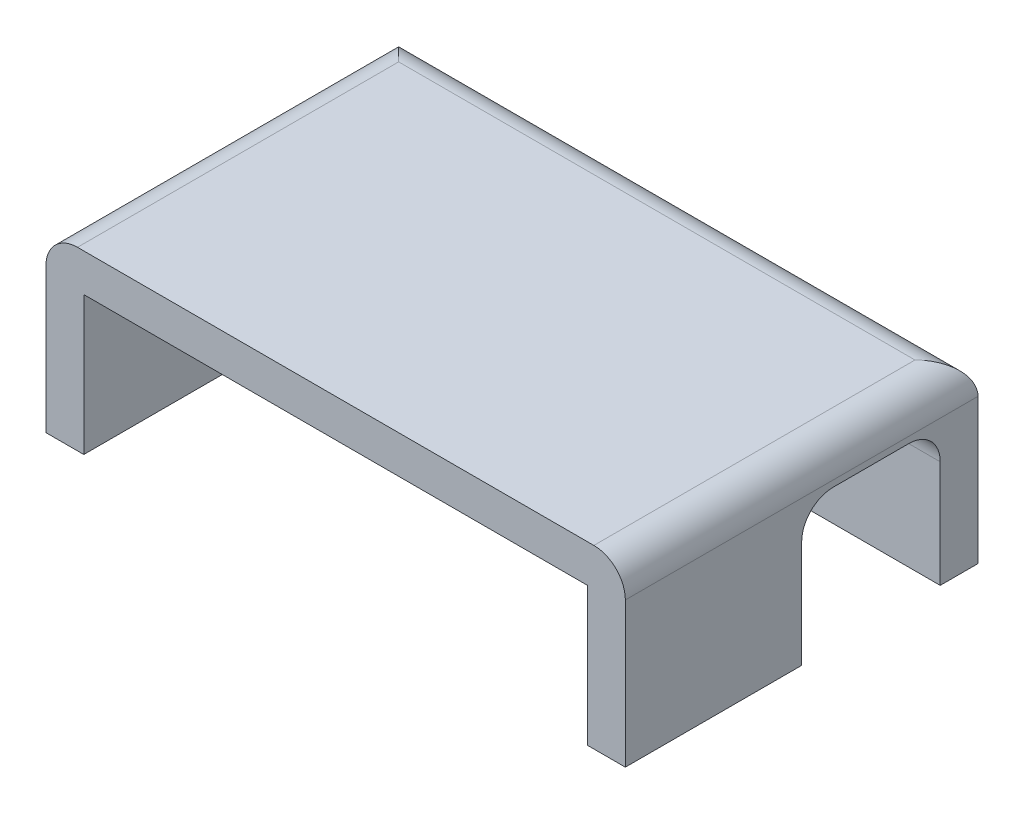
SolidWorks part; units mm, degrees
ref_plane "Alzado" through (0, 0, 0) normal (0, 0, 1) x (1, 0, 0)
ref_plane "Planta" through (0, 0, 0) normal (0, 1, 0) x (1, 0, 0)
ref_plane "Vista lateral" through (0, 0, 0) normal (1, 0, 0) x (0, 0, -1)
sketch "Croquis1" plane through (0, 0, 0) normal (0, 1, 0) x (1, 0, 0)
  line L1 (-40, 25) -> (0, 25)
  line L2 (-40, 25) -> (-40, 0)
  line L3 (-40, 0) -> (0, 0)
  line L4 (0, 25) -> (0, 0)
  line L5 (3, 0) -> (-43, 0)
  line L6 (3, 0) -> (3, 28)
  line L7 (3, 28) -> (-43, 28)
  line L8 (-43, 0) -> (-43, 28)
  dimension "D1" = 40
  dimension "D2" = 25
  dimension "D3" = 3
  dimension "D4" = 3
  dimension "D6" = 3
extrude "Saliente-Extruir1" add sketch "Croquis1" along normal blind 14 contours L8 L5 L2 L1 L4 L6 L7
sketch "Croquis2" plane through (0, 0, -25) normal (0, 0, 1) x (1, 0, 0)
  line L0 (0, 14) -> (0, 0) construction
  line L1 (-40, 14) -> (0, 14)
  line L2 (-40, 14) -> (-40, 11)
  line L3 (-40, 11) -> (0, 11)
  line L4 (0, 14) -> (0, 11)
  dimension "D1" = 3
extrude "Saliente-Extruir2" add sketch "Croquis2" along normal up to surface (25 mm away) up to face at (-41.5, 7, 0)
sketch "Croquis3" plane through (3, 0, 0) normal (1, 0, 0) x (0, 0, -1)
  line L0 (0, 0) -> (28, 0) construction
  line L1 (25, 0) -> (14, 0)
  line L2 (25, 0) -> (25, 11)
  line L3 (25, 11) -> (14, 11)
  line L4 (14, 0) -> (14, 11)
  line L6 (28, 14) -> (28, 0) construction
  line L7 (0, 14) -> (28, 14) construction
  dimension "D1" = 3
  dimension "D2" = 11
  dimension "D3" = 3
extrude "Cortar-Extruir1" cut sketch "Croquis3" against normal blind 12
fillet "Redondeo1" radius 2.5 5 edges at (3, 14, -14) (-43, 14, -14) (-20, 14, -28) (1.5, 11, -14) (-18.5, 11, -25)
